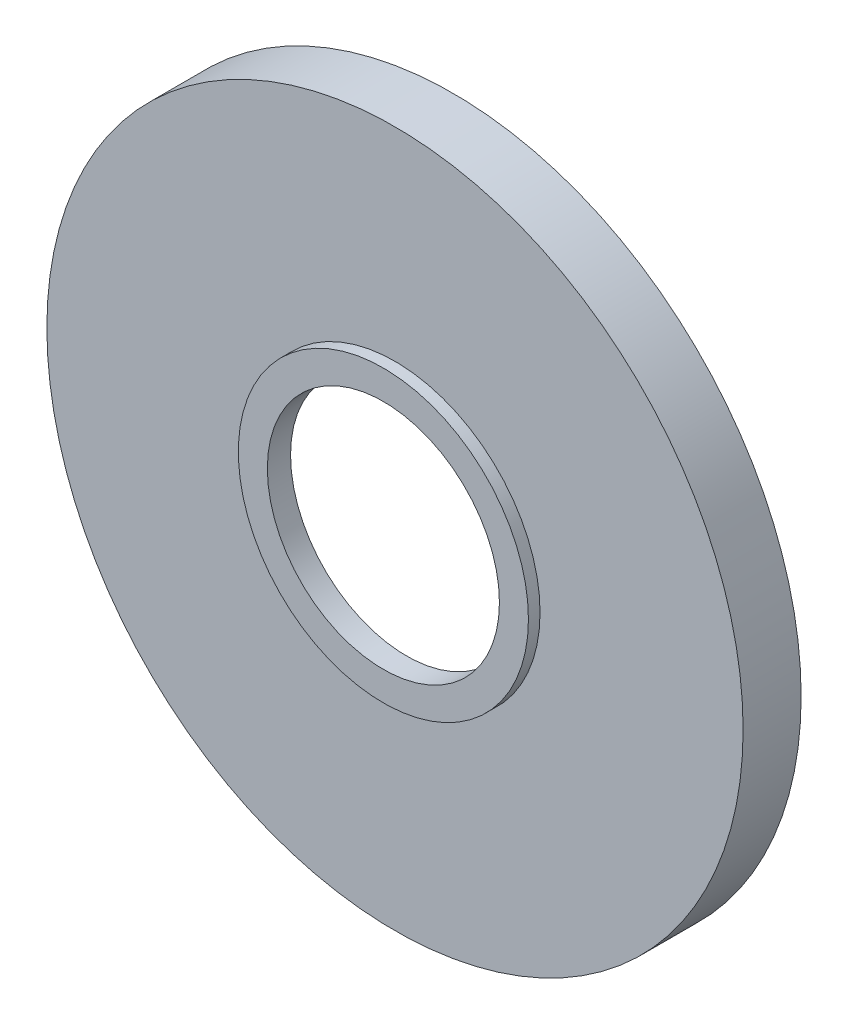
SolidWorks part; units mm, degrees
ref_plane "前视基准面" through (0, 0, 0) normal (0, 0, 1) x (1, 0, 0)
ref_plane "上视基准面" through (0, 0, 0) normal (0, 1, 0) x (1, 0, 0)
ref_plane "右视基准面" through (0, 0, 0) normal (1, 0, 0) x (0, 0, -1)
other "Configuration Table"
sketch "草图1" plane through (0, 0, 0) normal (0, 0, 1) x (1, 0, 0)
  circle A0 centre (0, 0) radius 60 construction
  circle A1 centre (0, 0) radius 60
extrude "拉伸-薄壁1" add sketch "草图1" along normal blind 8 thin thin type one direction reverse wall 3
sketch "草图2" plane through (0, 0, 8) normal (0, 0, 1) x (1, 0, 0)
  circle A0 centre (0, 0) radius 60 construction
  circle A1 centre (0, 0) radius 60
extrude "拉伸-薄壁2" add sketch "草图2" along normal blind 2 thin thin type one direction reverse wall 40
sketch "草图3" plane through (0, 0, 10) normal (0, 0, 1) x (1, 0, 0)
  circle A0 centre (0, 0) radius 20 construction
  circle A1 centre (0, 0) radius 20
extrude "拉伸-薄壁3" add sketch "草图3" along normal blind 2 thin
